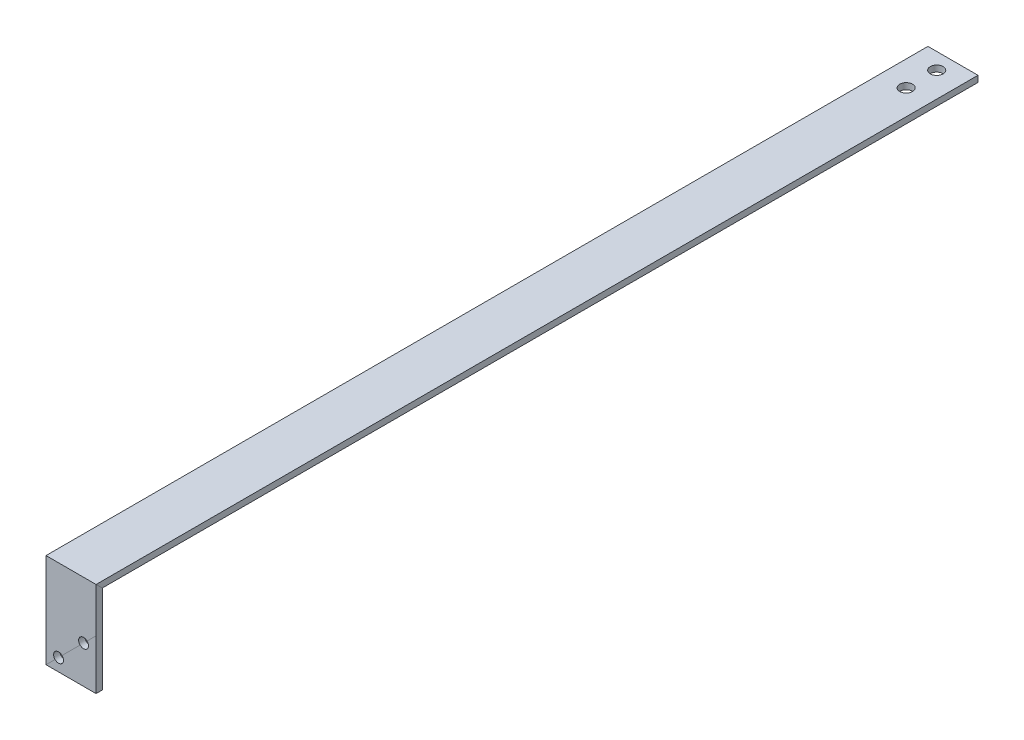
SolidWorks part; units mm, degrees
ref_plane "Alzado" through (0, 0, 0) normal (0, 0, 1) x (1, 0, 0)
ref_plane "Planta" through (0, 0, 0) normal (0, 1, 0) x (1, 0, 0)
ref_plane "Vista lateral" through (0, 0, 0) normal (1, 0, 0) x (0, 0, -1)
sketch "Croquis1" plane through (0, 0, 0) normal (0, 0, 1) x (1, 0, 0)
  line L1 (-25.4, 3.155) -> (25.4, 3.155)
  line L2 (-25.4, 3.155) -> (-25.4, -3.155)
  line L3 (-25.4, -3.155) -> (25.4, -3.155)
  line L4 (25.4, 3.155) -> (25.4, -3.155)
  line L5 (-25.4, 3.155) -> (25.4, -3.155) construction
  line L6 (-25.4, -3.155) -> (25.4, 3.155) construction
  point P0 (0, 0)
  dimension "D1" = 50.8
  dimension "D2" = 6.31
sketch3d "Croquis3D2"
  line L0 (0, 0, 0) -> (0, 0, 891.73)
  line L1 (0, 0, 891.73) -> (0, -67.38, 891.73)
  line L2 (0, -67.38, 891.73) -> (84.6, -67.38, 891.73)
  dimension "D1" = 891.73
  dimension "D2" = 67.38
  dimension "D3" = 84.6
sweep "Barrer1" add profiles "Croquis1" path "Croquis3D2"
sketch "Croquis2" plane through (0, 3.155, 0) normal (0, 1, 0) x (1, 0, 0)
  line L0 (0, -16.5) -> (0, -47.5) construction
  circle A0 centre (0, -16.5) radius 6.5
  circle A1 centre (0, -47.5) radius 6.5
  dimension "D1" = 13
  dimension "D2" = 13
extrude "Cortar-Extruir1" cut sketch "Croquis2" against normal blind 10
sketch "Croquis3" plane through (0, 0, 888.575) normal (0, 0, -1) x (-1, 0, 0)
  line L0 (-84.6, -67.38) -> (-60, -67.38) construction
  line L1 (0, -67.38) -> (-84.6, -67.38) construction
  circle A0 centre (-60, -67.38) radius 6.5
  dimension "D2" = 13
  dimension "D1" = 24.6
extrude "Cortar-Extruir2" cut sketch "Croquis3" against normal blind 10
sketch "Croquis4" plane through (0, 0, 894.885) normal (0, 0, 1) x (1, 0, 0)
  line L0 (25.4, -41.98) -> (25.4, -92.78)
  line L1 (-25.4, -92.78) -> (84.6, -92.78) construction
  line L2 (25.4, -92.78) -> (84.6, -92.78)
  line L3 (84.6, -92.78) -> (84.6, -41.98)
  line L4 (84.6, -41.98) -> (25.4, -41.98)
extrude "Cortar-Extruir3" cut sketch "Croquis4" against normal blind 10
sketch "Croquis5" plane through (0, 0, 888.575) normal (0, 0, -1) x (-1, 0, 0)
  line L0 (25.4, -92.78) -> (-25.4, -41.98) construction
  line L1 (-25.4, -41.98) -> (0, -67.38) construction
  line L2 (0, -67.38) -> (25.4, -67.38) construction
  line L3 (25.4, -3.155) -> (25.4, -92.78) construction
  line L4 (0, -67.38) -> (25.4, -92.78) construction
  line L5 (25.4, -92.78) -> (12.7, -80.08) construction
  line L6 (0, -67.38) -> (-25.4, -41.98) construction
  line L7 (-25.4, -41.98) -> (-12.7, -54.68) construction
  line L8 (-12.7, -54.68) -> (25.4, -54.68) construction
  circle A0 centre (-12.7, -54.68) radius 5
  circle A1 centre (12.7, -80.08) radius 5
  dimension "D1" = 10
  dimension "D2" = 10
extrude "Cortar-Extruir4" cut sketch "Croquis5" against normal blind 10
